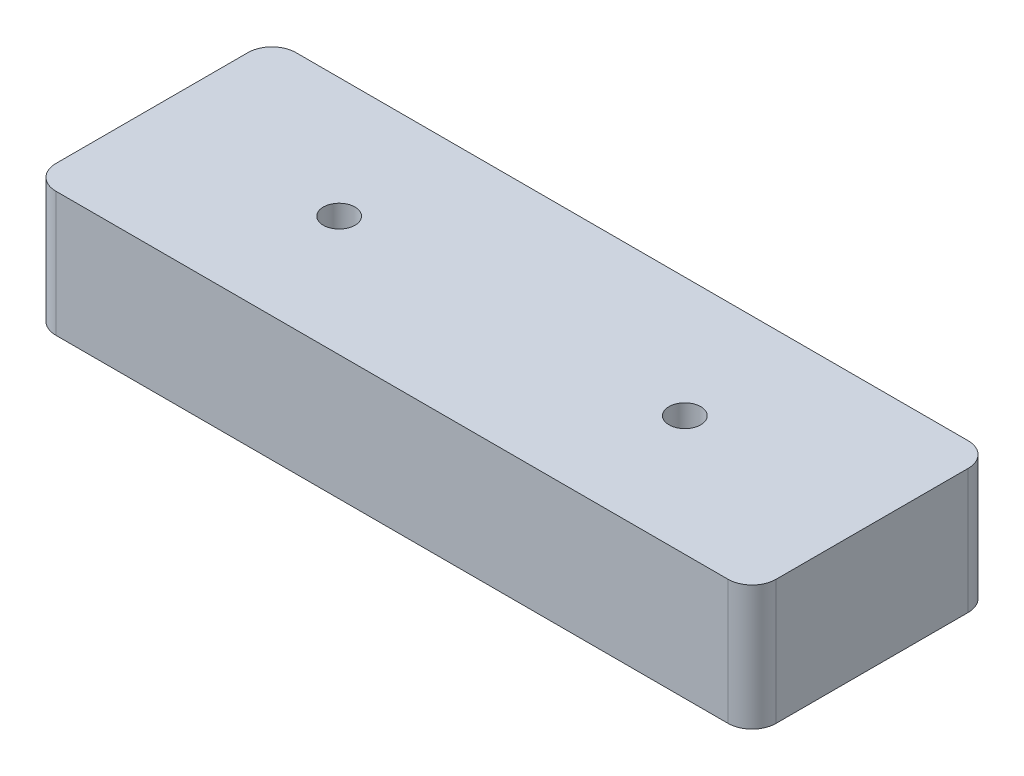
SolidWorks part; units mm, degrees
ref_plane "Front Plane" through (0, 0, 0) normal (0, 0, 1) x (1, 0, 0)
ref_plane "Top Plane" through (0, 0, 0) normal (0, 1, 0) x (1, 0, 0)
ref_plane "Right Plane" through (0, 0, 0) normal (1, 0, 0) x (0, 0, -1)
sketch "Sketch1" plane through (0, 0, 0) normal (0, 1, 0) x (1, 0, 0)
  line L1 (-37.5, 12.5) -> (37.5, 12.5)
  line L2 (-37.5, 12.5) -> (-37.5, -12.5)
  line L3 (-37.5, -12.5) -> (37.5, -12.5)
  line L4 (37.5, 12.5) -> (37.5, -12.5)
  line L5 (-37.5, 12.5) -> (37.5, -12.5) construction
  line L6 (-37.5, -12.5) -> (37.5, 12.5) construction
  point P0 (0, 0)
  dimension "D1" = 25
  dimension "D2" = 75
extrude "Boss-Extrude1" add sketch "Sketch1" along normal blind 13
hole_wizard "Tap Drill for M4x0.7 Tap1" positions "Sketch2" profile "Sketch3" hole size "M4x0.7" standard "ANSI Metric" end condition through all
sketch "Sketch2" plane through (0, 13, 0) normal (0, 1, 0) x (1, 0, 0)
  line L0 (-18, 0) -> (18, 0) construction
  point P0 (-18, 0)
  point P2 (18, 0)
  point P11 (0, 0)
  dimension "D1" = 36
sketch "Sketch3" plane through (-18, 13, 0) normal (1, 0, 0) x (0, 0, 1)
  line L0 (0, 0) -> (0, 13)
  line L1 (0, 13) -> (1.65, 13)
  line L2 (1.65, 13) -> (1.65, 0)
  line L5 (1.65, 0) -> (0, 0)
  line L11 (0, -6.35) -> (0, 107.95) construction
  dimension "Thru Hole Dia." = 3.3
  dimension "Thru Hole Depth" = 13
fillet "Fillet1" radius 2.5 4 edges at (37.5, 6.5, -12.5) (37.5, 6.5, 12.5) (-37.5, 6.5, -12.5) (-37.5, 6.5, 12.5)
